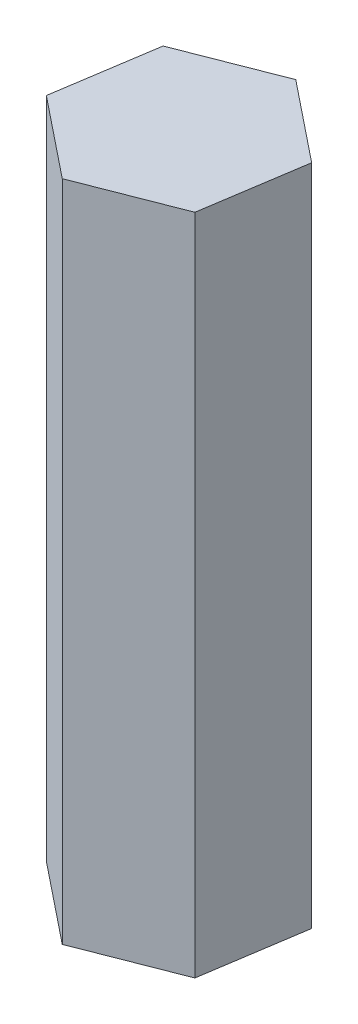
SolidWorks part; units mm, degrees
ref_plane "Front Plane" through (0, 0, 0) normal (0, 0, 1) x (1, 0, 0)
ref_plane "Top Plane" through (0, 0, 0) normal (0, 1, 0) x (1, 0, 0)
ref_plane "Right Plane" through (0, 0, 0) normal (1, 0, 0) x (0, 0, -1)
sketch "Sketch1" plane through (0, 0, 0) normal (0, 1, 0) x (1, 0, 0)
  line L1 (2.3358, 15.2697) -> (-12.0561, 9.6577)
  line L2 (-12.0561, 9.6577) -> (-14.3919, -5.612)
  line L3 (-14.3919, -5.612) -> (-2.3358, -15.2697)
  line L4 (-2.3358, -15.2697) -> (12.0561, -9.6577)
  line L5 (12.0561, -9.6577) -> (14.3919, 5.612)
  line L6 (14.3919, 5.612) -> (2.3358, 15.2697)
  circle A1 centre (0, 0) radius 13.3778 construction
extrude "Boss-Extrude1" add sketch "Sketch1" along normal blind 100
